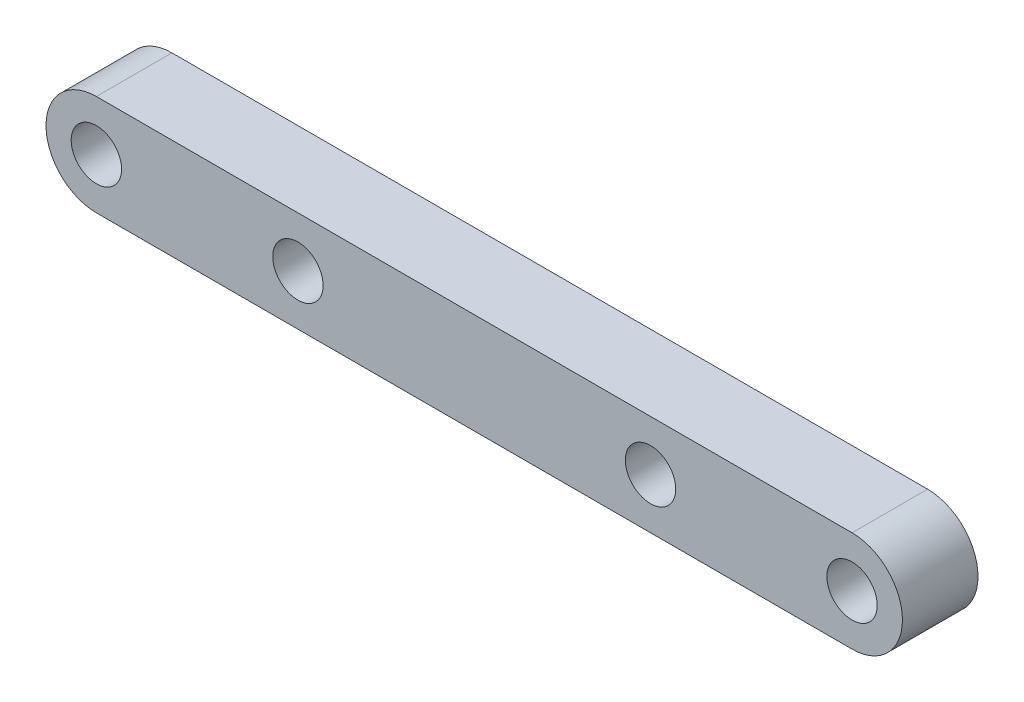
SolidWorks part; units mm, degrees
ref_plane "Front Plane" through (0, 0, 0) normal (0, 0, 1) x (1, 0, 0)
ref_plane "Top Plane" through (0, 0, 0) normal (0, 1, 0) x (1, 0, 0)
ref_plane "Right Plane" through (0, 0, 0) normal (1, 0, 0) x (0, 0, -1)
sketch "Sketch1" plane through (0, 0, 0) normal (0, 0, 1) x (1, 0, 0)
  line L0 (-15, 0) -> (15, 0) construction
  line L7 (-15, 2) -> (15, 2)
  line L8 (-15, -2) -> (15, -2)
  line L9 (0, 2) -> (0, -2) construction
  arc A6 (-15, 2) -> (-15, -2) centre (-15, 0) ccw
  arc A7 (15, -2) -> (15, 2) centre (15, 0) ccw
  circle A8 centre (15, 0) radius 1
  circle A9 centre (-15, 0) radius 1
  circle A10 centre (-7, 0) radius 1
  circle A11 centre (7, 0) radius 1
  point P2 (0, 0)
  dimension "D2" = 2
  dimension "D3" = 2
  dimension "D1" = 30
  dimension "D4" = 8
extrude "Boss-Extrude1" add sketch "Sketch1" along normal blind 3
